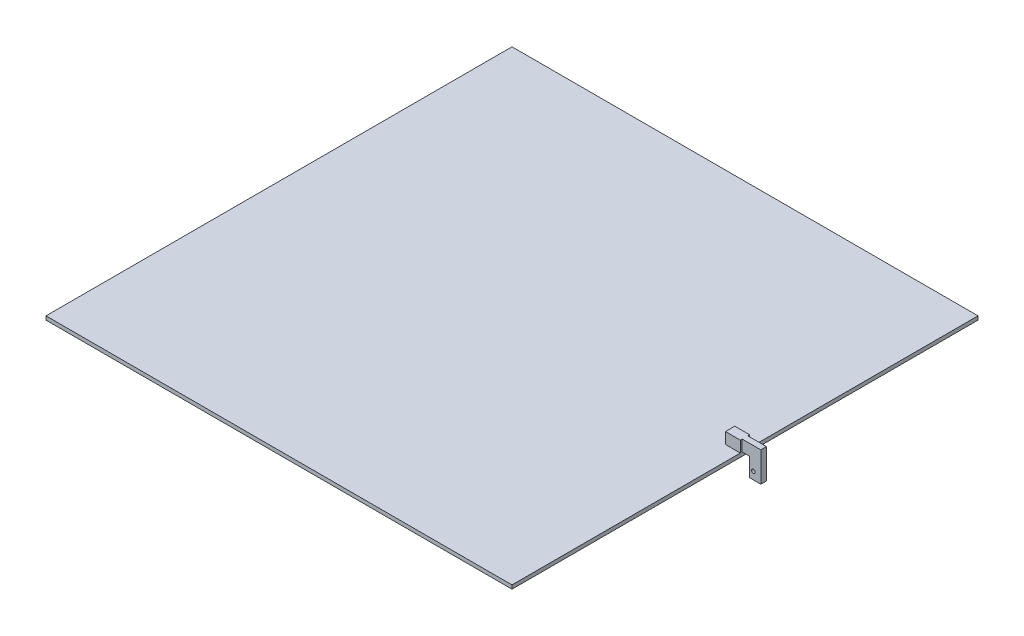
SolidWorks part; units mm, degrees
ref_plane "Alzado" through (0, 0, 0) normal (0, 0, 1) x (1, 0, 0)
ref_plane "Planta" through (0, 0, 0) normal (0, 1, 0) x (1, 0, 0)
ref_plane "Vista lateral" through (0, 0, 0) normal (1, 0, 0) x (0, 0, -1)
sketch "Croquis1" plane through (0, 0, 0) normal (0, 1, 0) x (1, 0, 0)
  line L1 (-125, 125) -> (125, 125)
  line L2 (-125, 125) -> (-125, -125)
  line L3 (-125, -125) -> (125, -125)
  line L4 (125, 125) -> (125, -125)
  line L5 (-125, 125) -> (125, -125) construction
  line L6 (-125, -125) -> (125, 125) construction
  point P0 (0, 0)
  dimension "D1" = 250
  dimension "D2" = 250
extrude "Saliente-Extruir1" add sketch "Croquis1" along normal blind 2
sketch "Croquis2" plane through (0, 2, 0) normal (0, 1, 0) x (1, 0, 0)
  line L0 (125, 2.5) -> (117, 2.5)
  line L1 (125, -125) -> (125, 125) construction
  line L2 (117, 2.5) -> (117, -2.5)
  line L3 (117, -2.5) -> (125, -2.5)
  line L4 (125, -2.5) -> (125, 2.5)
  point P6 (117, 0)
  dimension "D1" = 5
  dimension "D2" = 8
extrude "Saliente-Extruir2" add sketch "Croquis2" along normal blind 6
sketch "Croquis3" plane through (125, 0, 0) normal (1, 0, 0) x (0, 0, -1)
  line L0 (2.5, 8) -> (2.5, 2) construction
  line L1 (-2.5, 8) -> (2.5, 8)
  line L2 (-2.5, 8) -> (-2.5, 2)
  line L3 (-2.5, 2) -> (2.5, 2)
  line L4 (2.5, 8) -> (2.5, 2)
  dimension "D1" = 6
extrude "Saliente-Extruir3" add sketch "Croquis3" along normal blind 10
sketch "Croquis4" plane through (0, 2, 0) normal (0, -1, 0) x (1, 0, 0)
  line L0 (135, -2.5) -> (125, -2.5) construction
  line L1 (135, 2.5) -> (129, 2.5)
  line L2 (135, 2.5) -> (135, -2.5)
  line L3 (135, -2.5) -> (129, -2.5)
  line L4 (129, 2.5) -> (129, -2.5)
  dimension "D1" = 6
extrude "Saliente-Extruir4" add sketch "Croquis4" along normal blind 10
sketch "Croquis5" plane through (0, 0, -2.5) normal (0, 0, -1) x (-1, 0, 0)
  line L0 (-134.8628, 0.1326) -> (-124.8685, -0.2046) construction
  line L1 (-135, -8) -> (-135, 8) construction
  circle A0 centre (-131, -4) radius 0.983
  dimension "D1" = 4
  dimension "D2" = 4
extrude "Cortar-Extruir1" cut sketch "Croquis5" against normal up to next
sketch "Croquis6" plane through (0, 8, 0) normal (0, 1, 0) x (1, 0, 0)
  line L0 (135, -1.5) -> (125, -1.5)
  line L1 (135, 2.5) -> (135, -2.5) construction
  line L2 (125, -1.5) -> (125, -2.5)
  line L3 (117, -2.5) -> (135, -2.5) construction
  line L4 (125, -2.5) -> (135, -2.5)
  line L5 (135, -2.5) -> (135, -1.5)
  line L6 (135, 2.5) -> (125, 2.5)
  line L7 (125, 2.5) -> (125, 1.5)
  line L8 (125, 1.5) -> (135, 1.5)
  line L9 (135, 1.5) -> (135, 2.5)
  dimension "D1" = 1
  dimension "D2" = 1
  dimension "D3" = 10
extrude "Cortar-Extruir2" cut sketch "Croquis6" against normal up to next
